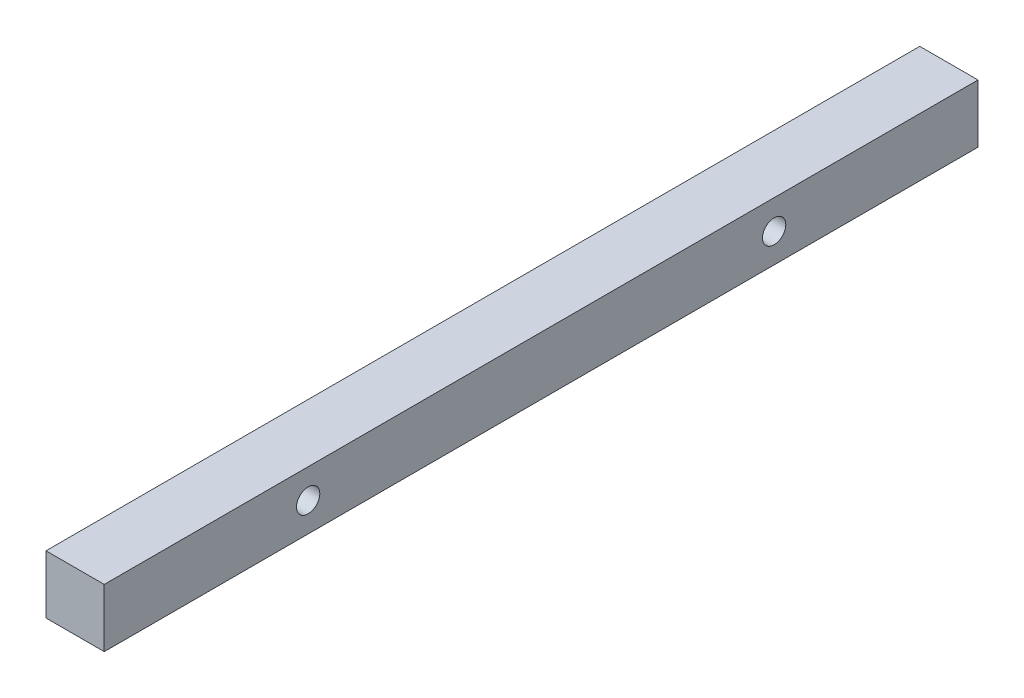
SolidWorks part; units mm, degrees
ref_plane "Alzado" through (0, 0, 0) normal (0, 0, 1) x (1, 0, 0)
ref_plane "Planta" through (0, 0, 0) normal (0, 1, 0) x (1, 0, 0)
ref_plane "Vista lateral" through (0, 0, 0) normal (1, 0, 0) x (0, 0, -1)
sketch "Croquis1" plane through (0, 0, 0) normal (0, 0, 1) x (1, 0, 0)
  line L1 (-10, -10) -> (10, -10)
  line L2 (-10, -10) -> (-10, 10)
  line L3 (-10, 10) -> (10, 10)
  line L4 (10, -10) -> (10, 10)
  line L5 (-10, -10) -> (10, 10) construction
  line L6 (-10, 10) -> (10, -10) construction
  point P0 (0, 0)
  dimension "D1" = 20
  dimension "D2" = 20
extrude "Saliente-Extruir1" add sketch "Croquis1" along normal mid plane 300
sketch "Croquis2" plane through (0, 0, 0) normal (1, 0, 0) x (0, 0, -1)
  line L0 (0, 10) -> (0, -10) construction
  line L1 (-150, 10) -> (150, 10) construction
  line L2 (-150, -10) -> (150, -10) construction
  line L3 (140, 10) -> (140, -10) construction
  line L4 (150, -10) -> (150, 10) construction
  line L5 (-140, 10) -> (-140, -10) construction
  circle A0 centre (0, 0) radius 2.5
  circle A1 centre (140, 0) radius 2.5
  circle A2 centre (-140, 0) radius 2.5
  point P8 (150, 0)
  dimension "D2" = 5
  dimension "D1" = 10
extrude "Cortar-Extruir1" cut sketch "Croquis2" against normal through all
sketch "Croquis3" plane through (-10, 0, 0) normal (-1, 0, 0) x (0, 0, 1)
  line L0 (0, 10) -> (0, -10) construction
  line L1 (150, 10) -> (-150, 10) construction
  line L2 (150, -10) -> (-150, -10) construction
  circle A0 centre (80, 0) radius 4
  circle A1 centre (-80, 0) radius 4
  dimension "D2" = 8
  dimension "D1" = 80
extrude "Cortar-Extruir2" cut sketch "Croquis3" against normal through all
